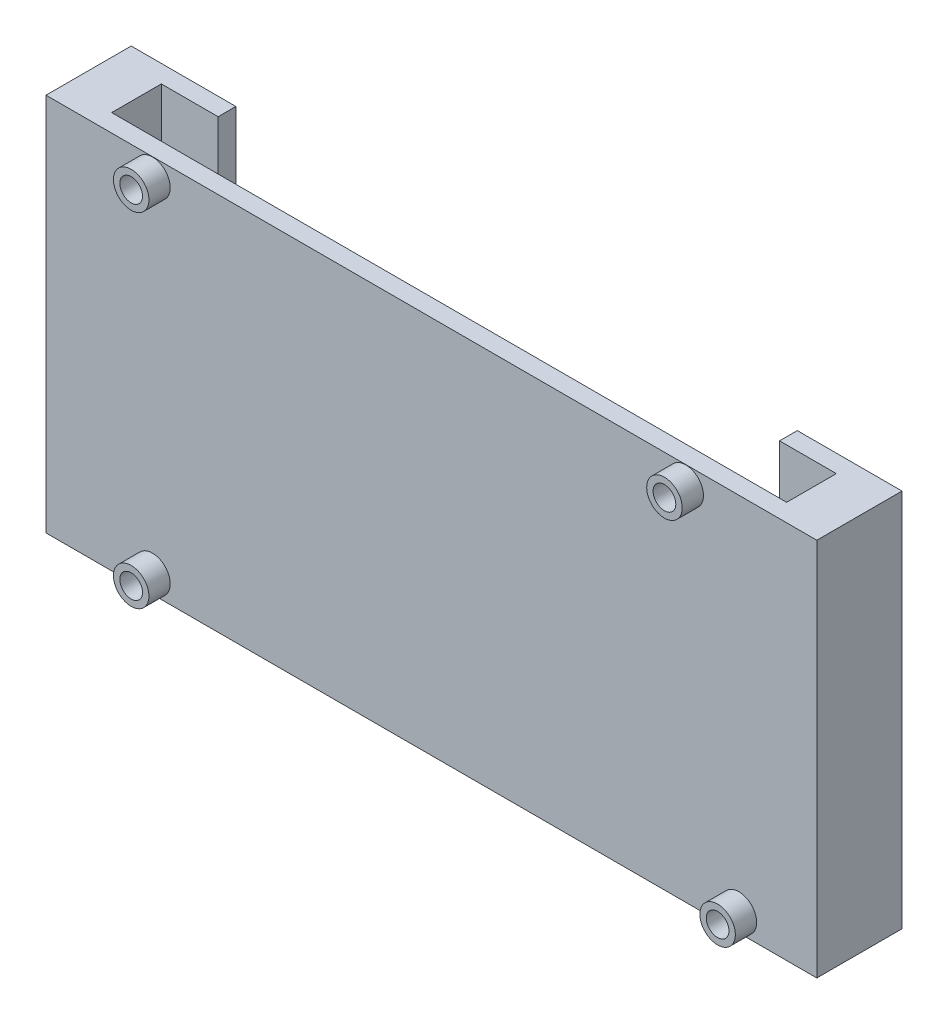
SolidWorks part; units mm, degrees
other "Markup1"
sketch "Sketch9" plane through (54.3, 26.7081, 7.5) normal (0.193, 0.975, 0.1103) x (0.9519, -0.1588, -0.262)
ref_plane "Front Plane" through (0, 0, 0) normal (0, 0, 1) x (1, 0, 0)
ref_plane "Top Plane" through (0, 0, 0) normal (0, 1, 0) x (1, 0, 0)
ref_plane "Right Plane" through (0, 0, 0) normal (1, 0, 0) x (0, 0, -1)
sketch "Sketch1" plane through (0, 0, 0) normal (0, 0, 1) x (1, 0, 0)
  line L1 (-54.3, -26.7081) -> (54.3, -26.7081)
  line L2 (-54.3, -26.7081) -> (-54.3, 26.7081)
  line L3 (-54.3, 26.7081) -> (54.3, 26.7081)
  line L4 (54.3, -26.7081) -> (54.3, 26.7081)
  line L5 (-54.3, -26.7081) -> (54.3, 26.7081) construction
  line L6 (-54.3, 26.7081) -> (54.3, -26.7081) construction
  point P0 (0, 0)
  dimension "D1" = 108.6
  dimension "D2" = 53.4162
extrude "Boss-Extrude1" add sketch "Sketch1" along normal blind 2.5
sketch "Sketch2" plane through (0, 0, 2.5) normal (0, 0, 1) x (1, 0, 0)
  line L0 (-54.3, 26.7081) -> (-54.3, -26.7081) construction
  line L1 (54.3, 26.7081) -> (-54.3, 26.7081) construction
  line L2 (-54.3, -26.7081) -> (54.3, -26.7081) construction
  circle A0 centre (-39.3, 24.1681) radius 2.5
  circle A1 centre (35.83, 24.1681) radius 2.5
  circle A2 centre (43.32, -24.1681) radius 2.5
  circle A3 centre (-39.3, -24.1681) radius 2.5
  dimension "D3" = 5
  dimension "D4" = 75.13
  dimension "D5" = 48.3362
  dimension "D6" = 15
  dimension "D2" = 2.54
  dimension "D7" = 82.62
  dimension "D8" = 2.54
extrude "Boss-Extrude2" add sketch "Sketch2" along normal blind 3
sketch "Sketch3" plane through (0, 0, 5.5) normal (0, 0, 1) x (1, 0, 0)
  circle A0 centre (35.83, 24.1681) radius 2.5 construction
  point P0 (-39.3, 24.1681)
  point P3 (35.83, 24.1681)
  point P5 (43.32, -24.1681)
  point P8 (-39.3, -24.1681)
hole_wizard "M3 Clearance Hole1" positions "Sketch3" profile "Sketch4" hole size "M3" standard "ANSI Metric" end condition through all
sketch "Sketch4" plane through (-39.3, 24.1681, 5.5) normal (1, 0, 0) x (0, -1, 0)
  line L0 (0, 0) -> (0, 5.5)
  line L1 (0, 5.5) -> (1.6, 5.5)
  line L2 (1.6, 5.5) -> (1.6, 0)
  line L5 (1.6, 0) -> (0, 0)
  line L11 (0, -6.35) -> (0, 107.95) construction
  dimension "Thru Hole Dia." = 3.2
  dimension "Thru Hole Depth" = 5.5
sketch "Sketch5" plane through (0, 0, 0) normal (0, 0, -1) x (-1, 0, 0)
  line L0 (54.3, -26.7081) -> (-54.3, -26.7081) construction
  line L1 (-54.3, 26.7081) -> (-47.55, 26.7081)
  line L2 (-54.3, 26.7081) -> (-54.3, -26.7081)
  line L3 (-54.3, -26.7081) -> (-47.55, -26.7081)
  line L4 (-47.55, 26.7081) -> (-47.55, -26.7081)
  line L6 (54.3, 26.7081) -> (47.55, 26.7081)
  line L7 (54.3, 26.7081) -> (54.3, -26.7081)
  line L8 (54.3, -26.7081) -> (47.55, -26.7081)
  line L9 (47.55, 26.7081) -> (47.55, -26.7081)
  dimension "D1" = 6.75
  dimension "D2" = 6.75
extrude "Boss-Extrude3" add sketch "Sketch5" along normal blind 9.5
sketch "Sketch6" plane through (47.55, 0, 0) normal (-1, 0, 0) x (0, 0, 1)
  line L0 (2.5, -26.7081) -> (-9.5, -26.7081) construction
  line L1 (-9.5, 26.7081) -> (-7, 26.7081)
  line L2 (-9.5, 26.7081) -> (-9.5, -26.7081)
  line L3 (-9.5, -26.7081) -> (-7, -26.7081)
  line L4 (-7, 26.7081) -> (-7, -26.7081)
  dimension "D1" = 2.5
extrude "Boss-Extrude4" add sketch "Sketch6" along normal blind 8
sketch "Sketch7" plane through (-47.55, 0, 0) normal (1, 0, 0) x (0, 0, -1)
  line L0 (-2.5, -26.7081) -> (9.5, -26.7081) construction
  line L1 (9.5, 26.7081) -> (7, 26.7081)
  line L2 (9.5, 26.7081) -> (9.5, -26.7081)
  line L3 (9.5, -26.7081) -> (7, -26.7081)
  line L4 (7, 26.7081) -> (7, -26.7081)
  dimension "D1" = 2.5
extrude "Boss-Extrude5" add sketch "Sketch7" along normal blind 8
sketch "Sketch8" plane through (0, -26.7081, 0) normal (0, -1, 0) x (1, 0, 0)
  line L0 (-54.3, -3.5) -> (54.3, -3.5) construction
  line L1 (-54.3, 2.5) -> (-54.3, -9.5) construction
  line L2 (54.3, 2.5) -> (54.3, -9.5) construction
  line L3 (-47.55, 0) -> (-54.3, 0) construction
  line L4 (-50.925, 0) -> (-50.925, -9.5) construction
  line L5 (-39.55, -9.5) -> (-54.3, -9.5) construction
  line L6 (47.55, 0) -> (54.3, 0) construction
  line L7 (50.925, 0) -> (50.925, -9.5) construction
  line L8 (54.3, -9.5) -> (39.55, -9.5) construction
  circle A0 centre (-50.925, -3.5) radius 3.15
  circle A1 centre (50.925, -3.5) radius 3.15
  dimension "D1" = 6.3
extrude "Cut-Extrude1" cut sketch "Sketch8" against normal blind 2.7
